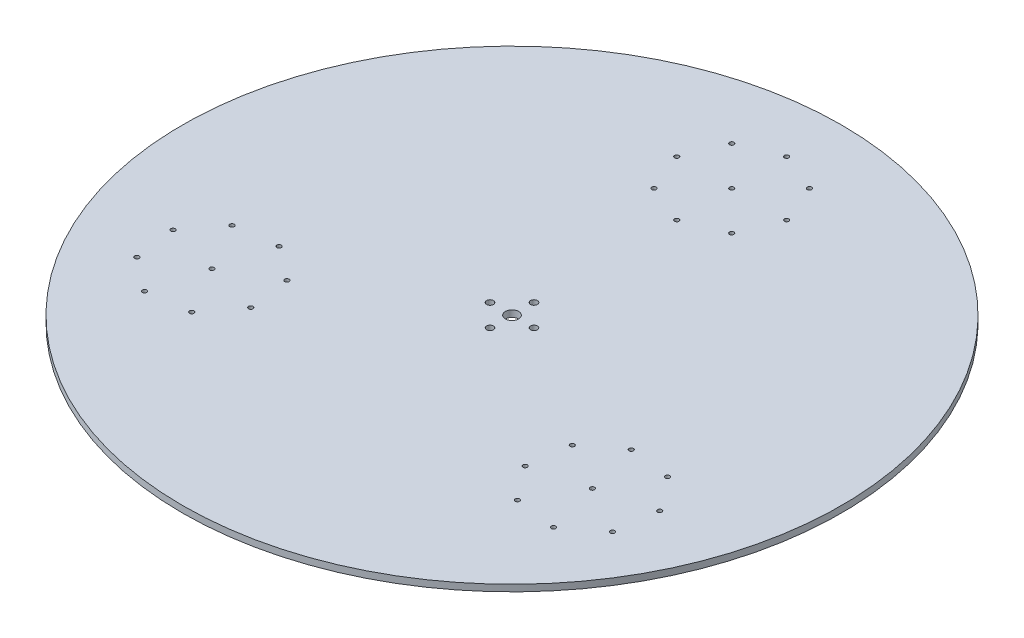
SolidWorks part; units mm, degrees
ref_plane "前视基准面" through (0, 0, 0) normal (0, 0, 1) x (1, 0, 0)
ref_plane "上视基准面" through (0, 0, 0) normal (0, 1, 0) x (1, 0, 0)
ref_plane "右视基准面" through (0, 0, 0) normal (1, 0, 0) x (0, 0, -1)
sketch "草图1" plane through (0, 0, 0) normal (0, 1, 0) x (1, 0, 0)
  circle A0 centre (0, 0) radius 150
  circle A1 centre (0, 0) radius 3
  circle A2 centre (0, 0) radius 10 construction
  circle A3 centre (0, 10) radius 1.55
  circle A4 centre (10, 0) radius 1.55
  circle A5 centre (0, -10) radius 1.55
  circle A6 centre (-10, 0) radius 1.55
  circle A7 centre (0, 0) radius 100 construction
  circle A8 centre (0, 100) radius 25 construction
  circle A9 centre (0, 125) radius 1
  circle A10 centre (17.6777, 117.6777) radius 1
  circle A11 centre (25, 100) radius 1
  circle A12 centre (17.6777, 82.3223) radius 1
  circle A13 centre (0, 75) radius 1
  circle A14 centre (-17.6777, 82.3223) radius 1
  circle A15 centre (-25, 100) radius 1
  circle A16 centre (-17.6777, 117.6777) radius 1
  circle A17 centre (0, 100) radius 1
  circle A18 centre (110.7507, -43.5295) radius 1
  circle A19 centre (0, 0) radius 150
  circle A20 centre (108.2532, -62.5) radius 1
  circle A21 centre (93.073, -74.1481) radius 1
  circle A22 centre (99.1025, -28.3494) radius 1
  circle A23 centre (86.6025, -50) radius 1
  circle A24 centre (80.1321, -25.8519) radius 1
  circle A25 centre (64.9519, -37.5) radius 1
  circle A26 centre (62.4544, -56.4705) radius 1
  circle A27 centre (74.1025, -71.6506) radius 1
  circle A28 centre (-93.073, -74.1481) radius 1
  circle A29 centre (0, 0) radius 150
  circle A30 centre (-108.2532, -62.5) radius 1
  circle A31 centre (-110.7507, -43.5295) radius 1
  circle A32 centre (-74.1025, -71.6506) radius 1
  circle A33 centre (-86.6025, -50) radius 1
  circle A34 centre (-62.4544, -56.4705) radius 1
  circle A35 centre (-64.9519, -37.5) radius 1
  circle A36 centre (-80.1321, -25.8519) radius 1
  circle A37 centre (-99.1025, -28.3494) radius 1
  point P16 (0, 0)
  point P35 (0, 100)
  point P76 (0, 0)
  dimension "D1" = 300
  dimension "D2" = 6
  dimension "D3" = 20
  dimension "D4" = 3.1
  dimension "D6" = 200
  dimension "D7" = 50
  dimension "D8" = 2
  dimension "D10" = 2
  dimension "D5" = 4
  dimension "D9" = 8
  dimension "D11" = 3
extrude "凸台-拉伸1" add sketch "草图1" along normal blind 3 contours A0 A37 A36 A35 A34 A33 A32 A31 A30 A28 A27 A26 A25 A24 A23 A22 A21 A20 A18 A17 A16 A15 A14 A13 A12 A11
